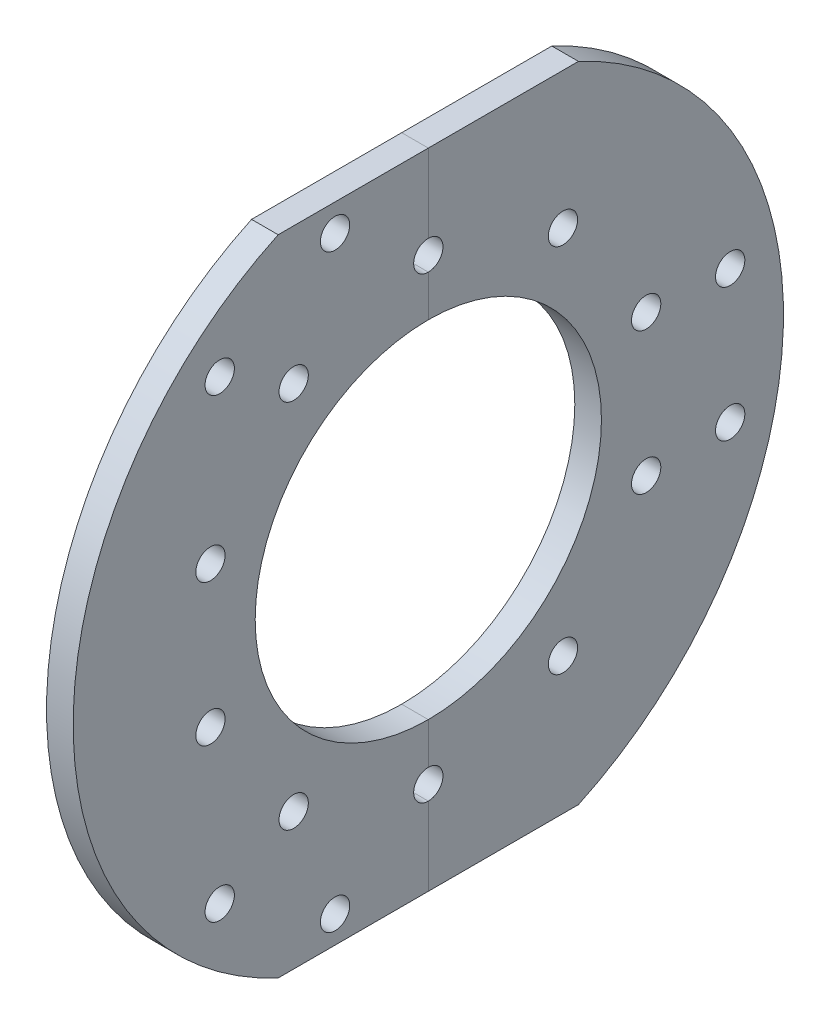
SolidWorks part; units mm, degrees
ref_plane "Front Plane" through (0, 0, 0) normal (0, 0, 1) x (1, 0, 0)
ref_plane "Top Plane" through (0, 0, 0) normal (0, 1, 0) x (1, 0, 0)
ref_plane "Right Plane" through (0, 0, 0) normal (1, 0, 0) x (0, 0, -1)
sketch "Sketch1" plane through (0, 0, 0) normal (1, 0, 0) x (0, 0, -1)
  line L0 (-33.8194, 72.5) -> (33.8194, 72.5)
  line L1 (0, 0) -> (80, 0) construction
  line L2 (0, 0) -> (0, 51.6) construction
  line L3 (-33.8194, -72.5) -> (33.8194, -72.5)
  line L4 (68, 15) -> (68, -15) construction
  circle A0 centre (0, 0) radius 51.6 construction
  circle A1 centre (0, 51.6) radius 3.3
  circle A2 centre (30.3297, 41.7453) radius 3.3
  circle A3 centre (49.0745, 15.9453) radius 3.3
  circle A4 centre (49.0745, -15.9453) radius 3.3
  circle A5 centre (30.3297, -41.7453) radius 3.3
  circle A6 centre (0, -51.6) radius 3.3
  circle A7 centre (-30.3297, -41.7453) radius 3.3
  circle A8 centre (-49.0745, -15.9453) radius 3.3
  circle A9 centre (-49.0745, 15.9453) radius 3.3
  circle A10 centre (-30.3297, 41.7453) radius 3.3
  circle A11 centre (0, 0) radius 39
  arc A12 (-33.8194, 72.5) -> (-33.8194, -72.5) centre (0, 0) ccw
  arc A13 (33.8194, -72.5) -> (33.8194, 72.5) centre (0, 0) ccw
  circle A14 centre (68, 15) radius 3.3
  circle A15 centre (68, -15) radius 3.3
  circle A16 centre (-46.9904, -51.3897) radius 3.3
  circle A17 centre (-21.0096, -66.3897) radius 3.3
  circle A18 centre (-21.0096, 66.3897) radius 3.3
  circle A19 centre (-46.9904, 51.3897) radius 3.3
  point P25 (0, 0)
  point P28 (0, 72.5)
  point P34 (68, 0)
  point P36 (-90.6271, -41.7453)
  point P37 (0, 0)
  point P47 (0, 0)
  dimension "FlangeBoltDiameter" = 103.2
  dimension "M6ClearanceDiameter" = 6.6
  dimension "InternalDiameter" = 78
  dimension "ExternalDiameter" = 160
  dimension "D2" = 6.6
  dimension "TangentFaceRadius" = 72.5
  dimension "StrutHoleSeparation" = 30
  dimension "StrutHoleOffsetRadius" = 68
  dimension "FlangeBoltNumber" = 10
  dimension "D3" = 3
extrude "Boss-Extrude1" add sketch "Sketch1" along normal blind 6 contours L3 A13 L0 A12 A19 A18 A17 A16 A15 A14 A1 A2 A3 A4 A5 A6 A7 A8 A9 A10 A11
sketch "Sketch2" plane through (6, 0, 0) normal (1, 0, 0) x (0, 0, -1)
  circle A0 centre (-30.3297, 41.7453) radius 3.75
  circle A1 centre (0, 51.6) radius 3.75
  circle A2 centre (30.3297, 41.7453) radius 3.75
  circle A3 centre (49.0745, 15.9453) radius 3.75
  circle A4 centre (49.0745, -15.9453) radius 3.75
  circle A5 centre (30.3297, -41.7453) radius 3.75
  circle A6 centre (0, -51.6) radius 3.75
  circle A7 centre (-30.3297, -41.7453) radius 3.75
  circle A8 centre (-49.0745, -15.9453) radius 3.75
  circle A9 centre (-49.0745, 15.9453) radius 3.75
  point P4 (-4.3146, -62.3689)
  point P5 (0, 0)
  point P23 (0, 0)
  dimension "WasherDiameter" = 7.5
  dimension "WasherNumber" = 10
split line "Split Line1" [suppressed]
sketch "Sketch3" plane through (0, 0, 0) normal (1, 0, 0) x (0, 0, -1)
  line L0 (-9.5144, -61.4795) -> (-48.4856, -38.9795)
  line L1 (58, 22.5) -> (78, 22.5)
  line L2 (58, 22.5) -> (58, -22.5)
  line L3 (58, -22.5) -> (78, -22.5)
  line L4 (78, 22.5) -> (78, -22.5)
  line L5 (-9.5144, -61.4795) -> (-19.5144, -78.8)
  line L6 (-19.5144, -78.8) -> (-58.4856, -56.3)
  line L7 (-48.4856, -38.9795) -> (-58.4856, -56.3)
  line L8 (-48.4856, 38.9795) -> (-9.5144, 61.4795)
  line L9 (-48.4856, 38.9795) -> (-58.4856, 56.3)
  line L10 (-58.4856, 56.3) -> (-19.5144, 78.8)
  line L11 (-9.5144, 61.4795) -> (-19.5144, 78.8)
  point P4 (58, 0)
  point P6 (68, 15)
  point P8 (68, 22.5)
  point P9 (-32.0441, -87.3911)
  point P11 (0, 0)
  point P19 (0, 0)
  dimension "D1" = 3
  dimension "StrutFlangeLength" = 45
  dimension "StrutFlangeWidth" = 20
split line "Split Line3" [suppressed]
split "Split1" trim tools "Front Plane" bodies to split 101 resulting bodies 105 106
equation "\"D2@Sketch1\"=\"M6ClearanceDiameter@Sketch1\""
equation "\"WasherNumber@Sketch2\"= \"FlangeBoltNumber@Sketch1\""
